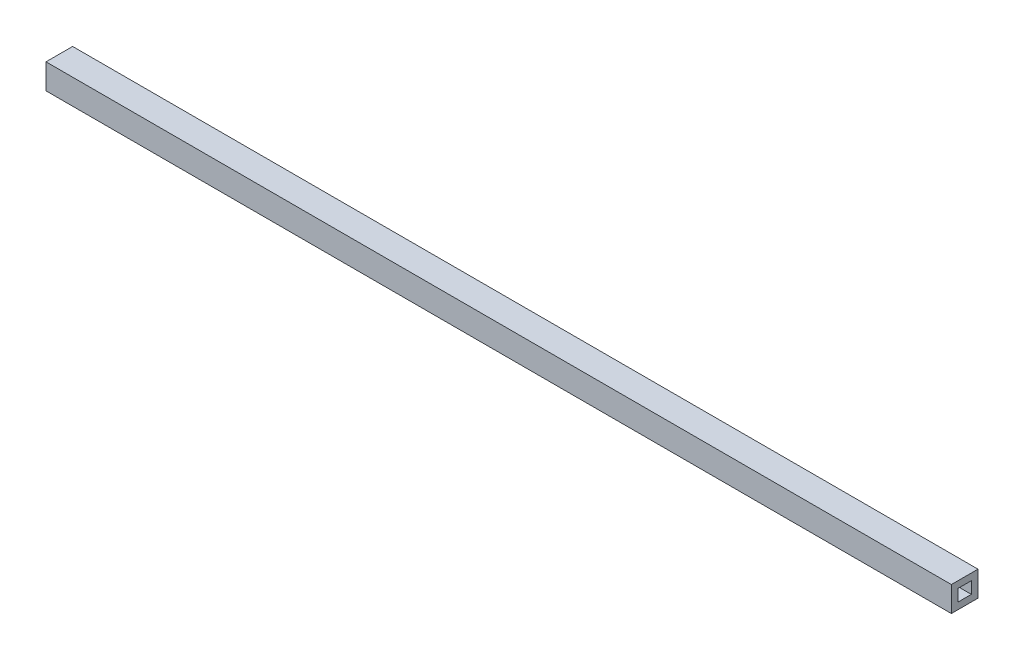
SolidWorks part; units mm, degrees
ref_plane "Front Plane" through (0, 0, 0) normal (0, 0, 1) x (1, 0, 0)
ref_plane "Top Plane" through (0, 0, 0) normal (0, 1, 0) x (1, 0, 0)
ref_plane "Right Plane" through (0, 0, 0) normal (1, 0, 0) x (0, 0, -1)
sketch "Sketch1" plane through (0, 0, 0) normal (0, 0, 1) x (1, 0, 0)
  line L1 (-431.8, 11.9944) -> (431.8, 11.9944)
  line L2 (-431.8, 11.9944) -> (-431.8, -11.9944)
  line L3 (-431.8, -11.9944) -> (431.8, -11.9944)
  line L4 (431.8, 11.9944) -> (431.8, -11.9944)
  line L5 (-431.8, 11.9944) -> (431.8, -11.9944) construction
  line L6 (-431.8, -11.9944) -> (431.8, 11.9944) construction
  point P0 (0, 0)
  dimension "D1" = 863.6
extrude "Boss-Extrude1" add sketch "Sketch1" along normal mid plane 25.4
sketch "Sketch2" plane through (431.8, 0, 0) normal (1, 0, 0) x (0, 0, -1)
  line L8 (6.35, -5.6444) -> (6.35, 5.6444)
  line L9 (6.35, 5.6444) -> (-6.35, 5.6444)
  line L10 (-6.35, 5.6444) -> (-6.35, -5.6444)
  line L11 (-6.35, -5.6444) -> (6.35, -5.6444)
  line L12 (6.35, -5.6444) -> (6.35, 5.6444)
  line L13 (6.35, 5.6444) -> (-6.35, 5.6444)
  line L14 (-6.35, 5.6444) -> (-6.35, -5.6444)
  line L15 (-6.35, -5.6444) -> (6.35, -5.6444)
  dimension "D1" = 6.35
extrude "Cut-Extrude1" cut sketch "Sketch2" against normal through all
